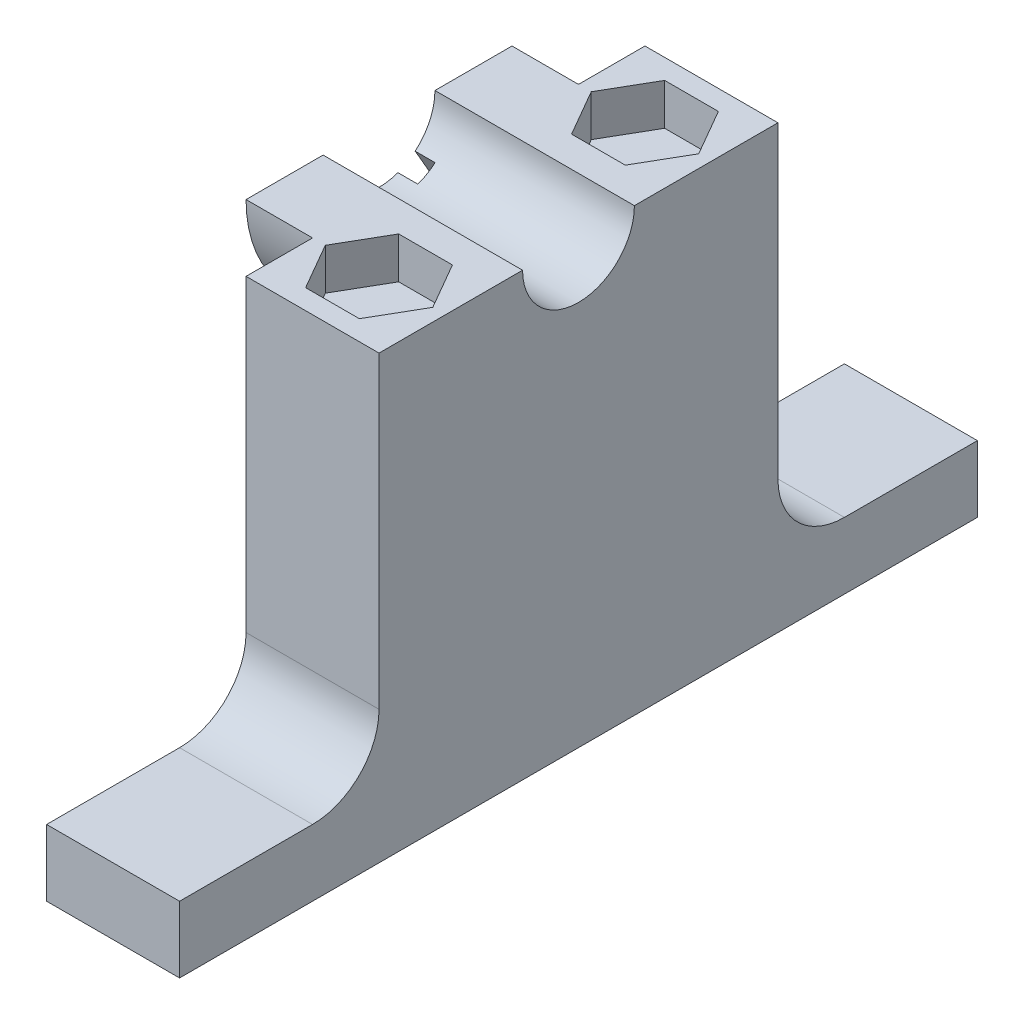
SolidWorks part; units mm, degrees
ref_plane "Front Plane" through (0, 0, 0) normal (0, 0, 1) x (1, 0, 0)
ref_plane "Top Plane" through (0, 0, 0) normal (0, 1, 0) x (1, 0, 0)
ref_plane "Right Plane" through (0, 0, 0) normal (1, 0, 0) x (0, 0, -1)
sketch "Sketch1" plane through (0, 0, 0) normal (0, 1, 0) x (1, 0, 0)
  line L1 (-5, -15) -> (5, -15)
  line L2 (-5, -15) -> (-5, 15)
  line L3 (-5, 15) -> (5, 15)
  line L4 (5, -15) -> (5, 15)
  point P5 (0, -15)
  point P9 (5, 0)
  dimension "D1" = 10
  dimension "D2" = 30
extrude "Boss-Extrude1" add sketch "Sketch1" along normal blind 33.2
sketch "Sketch2" plane through (-5, 0, 0) normal (-1, 0, 0) x (0, 0, 1)
  line L0 (-15, 33.2) -> (15, 33.2) construction
  circle A0 centre (0, 33.2) radius 4.205
  dimension "D1" = 8.41
extrude "Cut-Extrude1" cut sketch "Sketch2" against normal through all
sketch "Sketch3" plane through (0, 33.2, 0) normal (0, 1, 0) x (1, 0, 0)
  line L0 (5, 15) -> (-5, 15) construction
  line L1 (2.0207, 6.5) -> (4.0415, 10)
  line L2 (4.0415, 10) -> (2.0207, 13.5)
  line L3 (2.0207, 13.5) -> (-2.0207, 13.5)
  line L4 (-2.0207, 13.5) -> (-4.0415, 10)
  line L5 (-4.0415, 10) -> (-2.0207, 6.5)
  line L6 (-2.0207, 6.5) -> (2.0207, 6.5)
  circle A0 centre (0, 10) radius 3.5 construction
  point P11 (0, 15)
  dimension "D1" = 5
  dimension "D2" = 7
extrude "Cut-Extrude2" cut sketch "Sketch3" against normal blind 3.12
mirror "Mirror1" about plane through (0, 0, 0) normal (0, 0, 1) of "Cut-Extrude2"
sketch "Sketch4" plane through (5, 0, 0) normal (1, 0, 0) x (0, 0, -1)
  line L0 (-15, 0) -> (15, 0) construction
  line L1 (-30, 0) -> (30, 0)
  line L2 (-30, 0) -> (-30, 5)
  line L3 (-30, 5) -> (30, 5)
  line L4 (30, 0) -> (30, 5)
  point P4 (0, 0)
  dimension "D1" = 60
  dimension "D2" = 5
extrude "Boss-Extrude2" add sketch "Sketch4" against normal up to surface (10 mm away) up to face at (-5, 21.4325, 0)
fillet "Fillet1" radius 5 2 edges at (0, 5, -15) (0, 5, 15)
sketch "Sketch5" plane through (-5, 0, 0) normal (-1, 0, 0) x (0, 0, 1)
  line L0 (-15, 33.2) -> (-4.205, 33.2) construction
  line L1 (-10, 33.2) -> (-4.205, 33.2)
  line L2 (4.205, 33.2) -> (15, 33.2) construction
  line L3 (4.205, 33.2) -> (10, 33.2)
  arc A0 (-10, 33.2) -> (10, 33.2) centre (0, 33.2) ccw
  arc A1 (-4.205, 33.2) -> (4.205, 33.2) centre (0, 33.2) ccw construction
  arc A2 (-4.205, 33.2) -> (4.205, 33.2) centre (0, 33.2) ccw
  dimension "D1" = 20
extrude "Boss-Extrude3" add sketch "Sketch5" along normal blind 5
sketch "Sketch6" plane through (-10, 0, 0) normal (-1, 0, 0) x (0, 0, 1)
  line L0 (0, 33.2) -> (5, 24.5397)
  arc A0 (-10, 33.2) -> (10, 33.2) centre (0, 33.2) ccw construction
  dimension "D1" = 30
extrude "Cut-Extrude-Thin1" cut sketch "Sketch6" against normal blind 1.5 and the other way through all thin thin type mid plane wall 1.5
sketch "Sketch7" plane through (-10, 0, 0) normal (-1, 0, 0) x (0, 0, 1)
  line L0 (0, 33.2) -> (-5, 24.5397)
  arc A0 (-10, 33.2) -> (4.3364, 24.1891) centre (0, 33.2) ccw construction
  dimension "D1" = 30
extrude "Cut-Extrude-Thin2" cut sketch "Sketch7" against normal blind 1.5 and the other way through all thin thin type mid plane wall 1.5
